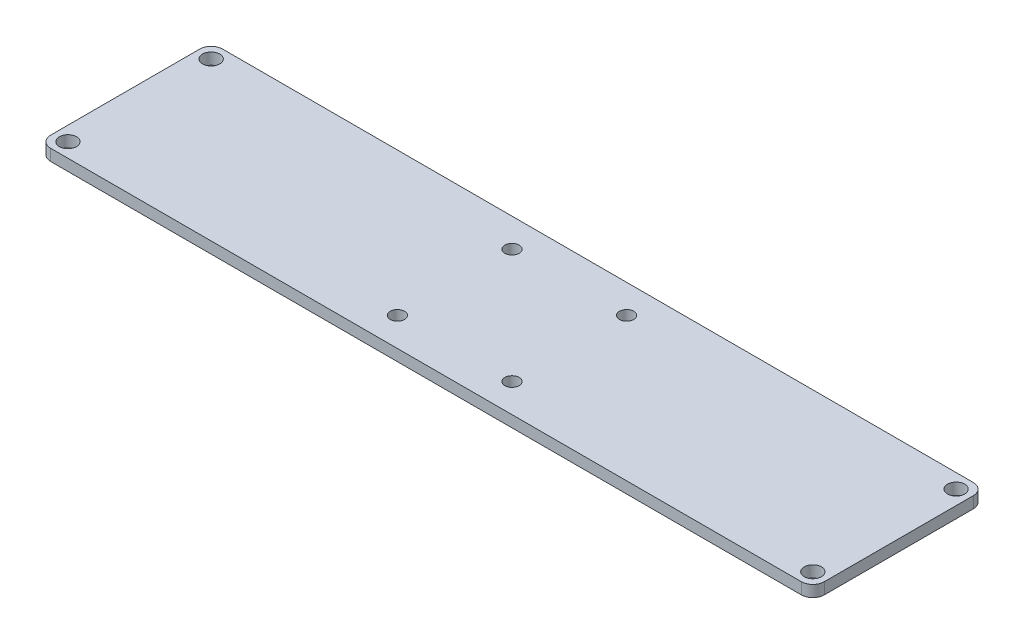
SolidWorks part; units mm, degrees
ref_plane "前视基准面" through (0, 0, 0) normal (0, 0, 1) x (1, 0, 0)
ref_plane "上视基准面" through (0, 0, 0) normal (0, 1, 0) x (1, 0, 0)
ref_plane "右视基准面" through (0, 0, 0) normal (1, 0, 0) x (0, 0, -1)
sketch "草图1" plane through (0, 0, 0) normal (0, 1, 0) x (1, 0, 0)
  line L1 (-56.0845, 17.0583) -> (78.9155, 17.0583)
  line L2 (-56.0845, 17.0583) -> (-56.0845, -12.9417)
  line L3 (-56.0845, -12.9417) -> (78.9155, -12.9417)
  line L4 (78.9155, 17.0583) -> (78.9155, -12.9417)
  circle A0 centre (-53.5845, 14.5583) radius 1.5
  circle A1 centre (-53.5845, -10.4417) radius 1.5
  circle A2 centre (76.4155, 14.5583) radius 1.5
  circle A3 centre (76.4155, -10.4417) radius 1.5
  dimension "D3" = 3
  dimension "D4" = 3
  dimension "D5" = 3
  dimension "D6" = 3
  dimension "D7" = 25
  dimension "D8" = 25
  dimension "D9" = 2.5
  dimension "D10" = 2.5
  dimension "D11" = 2.5
  dimension "D1" = 30
  dimension "D2" = 135
  dimension "D12" = 2.5
extrude "凸台-拉伸1" add sketch "草图1" along normal blind 2
fillet "圆角1" radius 2 4 edges at (78.9155, 1, -17.0583) (78.9155, 1, 12.9417) (-56.0845, 1, 12.9417) (-56.0845, 1, -17.0583)
sketch "草图2" plane through (0, 0, 0) normal (0, -1, 0) x (1, 0, 0)
  line L0 (-54.0845, 12.9417) -> (76.9155, 12.9417) construction
  line L1 (78.9155, 10.9417) -> (78.9155, -15.0583) construction
  circle A0 centre (1.4155, 7.9417) radius 1.25
  circle A1 centre (21.4155, 7.9417) radius 1.25
  circle A2 centre (1.4155, -12.0583) radius 1.25
  circle A3 centre (21.4155, -12.0583) radius 1.25
  dimension "D1" = 20
  dimension "D2" = 20
  dimension "D3" = 20
  dimension "D4" = 20
  dimension "D5" = 20
  dimension "D6" = 5
  dimension "D7" = 57.5
extrude "切除-拉伸1" cut sketch "草图2" against normal blind 2
